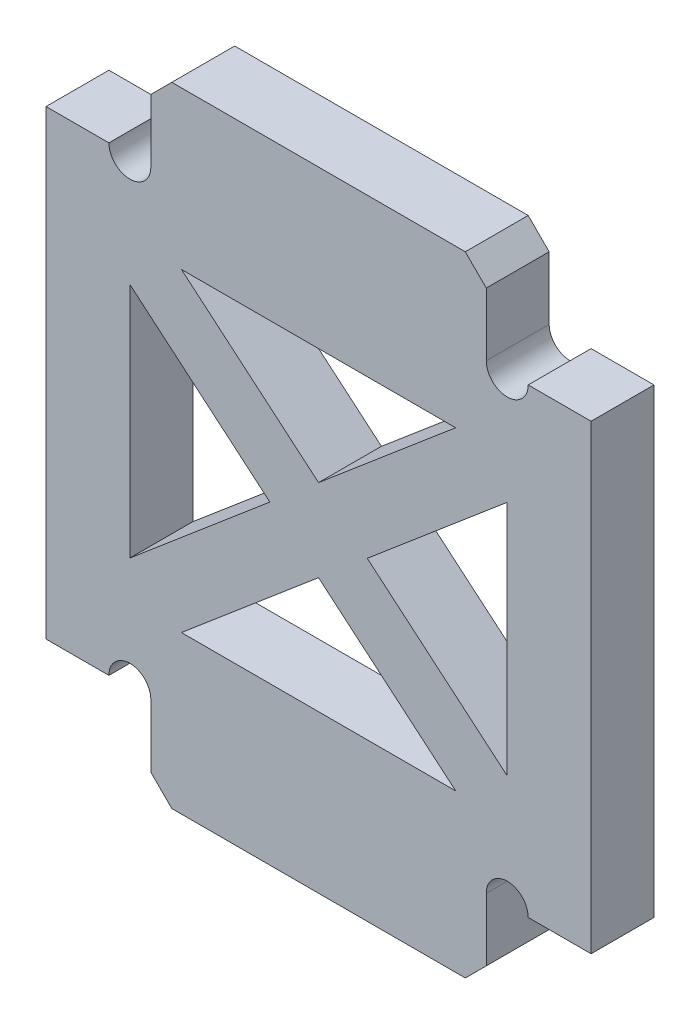
SolidWorks part; units mm, degrees
material "碳板"
ref_plane "前视基准面" through (0, 0, 0) normal (0, 0, 1) x (1, 0, 0)
ref_plane "上视基准面" through (0, 0, 0) normal (0, 1, 0) x (1, 0, 0)
ref_plane "右视基准面" through (0, 0, 0) normal (1, 0, 0) x (0, 0, -1)
sketch "草图1" plane through (0, 0, 0) normal (0, 0, 1) x (1, 0, 0)
  line L0 (0, 19.9183) -> (0, -17.9901) construction
  line L1 (-13, 11) -> (13, 11)
  line L2 (-13, 11) -> (-13, -11)
  line L3 (-13, -11) -> (13, -11)
  line L4 (13, 11) -> (13, -11)
  line L5 (-13, 11) -> (13, -11) construction
  line L6 (-13, -11) -> (13, 11) construction
  line L7 (-22.5399, 0) -> (24.3637, 0) construction
  line L8 (-8, 11) -> (-8, 15)
  line L9 (-8, 15) -> (8, 15)
  line L10 (8, 11) -> (8, 15)
  line L11 (8, -11) -> (8, -15)
  line L12 (-8, -15) -> (8, -15)
  line L13 (-8, -11) -> (-8, -15)
  line L14 (6.5414, 7.5) -> (-6.5414, 7.5)
  line L15 (-6.5414, 7.5) -> (0, 1.9649)
  line L16 (-2.3222, 0) -> (-9, 5.6505)
  line L17 (-9, 5.6505) -> (-9, -5.6505)
  line L18 (6.5414, 7.5) -> (0, 1.9649)
  line L19 (2.3222, 0) -> (9, 5.6505)
  line L20 (9, 5.6505) -> (9, -5.6505)
  line L21 (2.3222, 0) -> (9, -5.6505)
  line L22 (6.5414, -7.5) -> (-6.5414, -7.5)
  line L23 (-6.5414, -7.5) -> (0, -1.9649)
  line L24 (6.5414, -7.5) -> (0, -1.9649)
  line L25 (-2.3222, 0) -> (-9, -5.6505)
  circle A0 centre (-9, 11) radius 1
  circle A1 centre (9, 11) radius 1
  circle A2 centre (9, -11) radius 1
  circle A3 centre (-9, -11) radius 1
  point P0 (0, 0)
  point P15 (0, 15)
  point P34 (0, 7.5)
  point P38 (9, 0)
  point P42 (-9, 0)
  dimension "D4" = 2
  dimension "D1" = 30
  dimension "D2" = 4
  dimension "D3" = 16
  dimension "D5" = 4
  dimension "D6" = 1.5
  dimension "D7" = 1.5
  dimension "D8" = 4
  dimension "D9" = 3.5
extrude "凸台-拉伸1" add sketch "草图1" along normal mid plane 3 contours L3 A3 A2 L4 L1 A1 A0 L2 L24 L22 L23 L21 L19 L20 L14 L18 L15 L16 L25 L17 | L1 L10 L9 L8 | L3 L13 L12 L11
chamfer "倒角1" distance 1 angle 45 4 edges at (8, -15, 0) (-8, -15, 0) (8, 15, 0) (-8, 15, 0)
